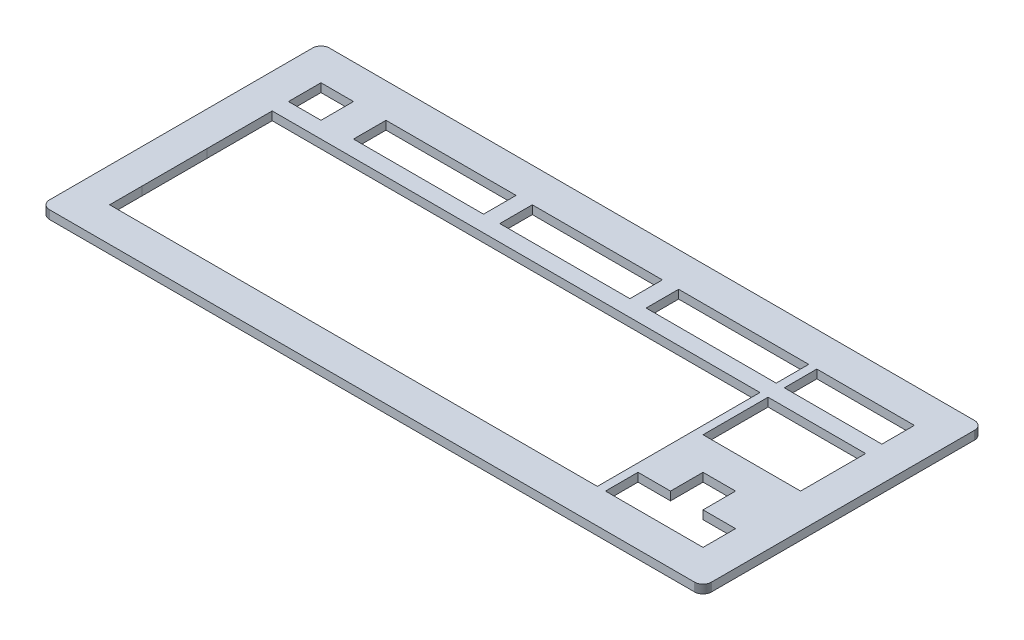
SolidWorks part; units mm, degrees
ref_plane "Front Plane" through (0, 0, 0) normal (0, 0, 1) x (1, 0, 0)
ref_plane "Top Plane" through (0, 0, 0) normal (0, 1, 0) x (1, 0, 0)
ref_plane "Right Plane" through (0, 0, 0) normal (1, 0, 0) x (0, 0, -1)
sketch "Sketch2" plane through (0, 0, 0) normal (0, 1, 0) x (1, 0, 0)
  line L0 (382.958, 164.299) -> (383.35, 164.284)
  line L1 (383.35, 164.284) -> (383.741, 164.237)
  line L2 (383.741, 164.237) -> (384.126, 164.162)
  line L3 (384.126, 164.162) -> (384.503, 164.055)
  line L4 (384.503, 164.055) -> (384.87, 163.919)
  line L5 (384.87, 163.919) -> (385.226, 163.755)
  line L6 (385.226, 163.755) -> (385.572, 163.564)
  line L7 (385.572, 163.564) -> (385.897, 163.344)
  line L8 (385.897, 163.344) -> (386.203, 163.102)
  line L9 (386.203, 163.102) -> (386.493, 162.834)
  line L10 (386.493, 162.834) -> (386.761, 162.547)
  line L11 (386.761, 162.547) -> (387.004, 162.238)
  line L12 (387.004, 162.238) -> (387.223, 161.913)
  line L13 (387.223, 161.913) -> (387.414, 161.569)
  line L14 (387.414, 161.569) -> (387.576, 161.212)
  line L15 (387.576, 161.212) -> (387.713, 160.845)
  line L16 (387.713, 160.845) -> (387.819, 160.467)
  line L17 (387.819, 160.467) -> (387.897, 160.082)
  line L18 (387.897, 160.082) -> (387.943, 159.693)
  line L19 (387.943, 159.693) -> (387.96, 159.299)
  line L20 (387.96, 159.299) -> (387.96, 5.2724)
  line L21 (387.96, 5.2724) -> (387.943, 4.881)
  line L22 (387.943, 4.881) -> (387.897, 4.491)
  line L23 (387.897, 4.491) -> (387.819, 4.1066)
  line L24 (387.819, 4.1066) -> (387.713, 3.7276)
  line L25 (387.713, 3.7276) -> (387.576, 3.3597)
  line L26 (387.576, 3.3597) -> (387.414, 3.0041)
  line L27 (387.414, 3.0041) -> (387.223, 2.661)
  line L28 (387.223, 2.661) -> (387.004, 2.3344)
  line L29 (387.004, 2.3344) -> (386.761, 2.0257)
  line L30 (386.761, 2.0257) -> (386.493, 1.7377)
  line L31 (386.493, 1.7377) -> (386.203, 1.4704)
  line L32 (386.203, 1.4704) -> (385.897, 1.2278)
  line L33 (385.897, 1.2278) -> (385.572, 1.0101)
  line L34 (385.572, 1.0101) -> (385.226, 0.8186)
  line L35 (385.226, 0.8186) -> (384.87, 0.6546)
  line L36 (384.87, 0.6546) -> (384.503, 0.5181)
  line L37 (384.503, 0.5181) -> (384.126, 0.412)
  line L38 (384.126, 0.412) -> (383.741, 0.3349)
  line L39 (383.741, 0.3349) -> (383.35, 0.2894)
  line L40 (383.35, 0.2894) -> (382.958, 0.2729)
  line L41 (382.958, 0.2729) -> (5.096, 0.2729)
  line L42 (5.096, 0.2729) -> (4.7019, 0.2894)
  line L43 (4.7019, 0.2894) -> (4.3119, 0.3349)
  line L44 (4.3119, 0.3349) -> (3.9274, 0.412)
  line L45 (3.9274, 0.412) -> (3.5498, 0.5181)
  line L46 (3.5498, 0.5181) -> (3.1819, 0.6546)
  line L47 (3.1819, 0.6546) -> (2.825, 0.8186)
  line L48 (2.825, 0.8186) -> (2.4819, 1.0101)
  line L49 (2.4819, 1.0101) -> (2.1566, 1.2278)
  line L50 (2.1566, 1.2278) -> (1.848, 1.4704)
  line L51 (1.848, 1.4704) -> (1.5599, 1.7377)
  line L52 (1.5599, 1.7377) -> (1.2926, 2.0257)
  line L53 (1.2926, 2.0257) -> (1.0501, 2.3344)
  line L54 (1.0501, 2.3344) -> (0.831, 2.661)
  line L55 (0.831, 2.661) -> (0.6394, 3.0041)
  line L56 (0.6394, 3.0041) -> (0.4754, 3.3597)
  line L57 (0.4754, 3.3597) -> (0.339, 3.7276)
  line L58 (0.339, 3.7276) -> (0.2329, 4.1066)
  line L59 (0.2329, 4.1066) -> (0.1571, 4.491)
  line L60 (0.1571, 4.491) -> (0.1102, 4.881)
  line L61 (0.1102, 4.881) -> (0.0951, 5.2737)
  line L62 (0.0951, 5.2737) -> (0.0951, 159.299)
  line L63 (0.0951, 159.299) -> (0.1102, 159.693)
  line L64 (0.1102, 159.693) -> (0.1571, 160.082)
  line L65 (0.1571, 160.082) -> (0.2329, 160.467)
  line L66 (0.2329, 160.467) -> (0.339, 160.845)
  line L67 (0.339, 160.845) -> (0.4754, 161.212)
  line L68 (0.4754, 161.212) -> (0.6394, 161.569)
  line L69 (0.6394, 161.569) -> (0.831, 161.913)
  line L70 (0.831, 161.913) -> (1.0501, 162.238)
  line L71 (1.0501, 162.238) -> (1.2926, 162.547)
  line L72 (1.2926, 162.547) -> (1.5599, 162.834)
  line L73 (1.5599, 162.834) -> (1.848, 163.102)
  line L74 (1.848, 163.102) -> (2.1566, 163.344)
  line L75 (2.1566, 163.344) -> (2.4819, 163.564)
  line L76 (2.4819, 163.564) -> (2.825, 163.755)
  line L77 (2.825, 163.755) -> (3.1819, 163.919)
  line L78 (3.1819, 163.919) -> (3.5498, 164.055)
  line L79 (3.5498, 164.055) -> (3.9274, 164.162)
  line L80 (3.9274, 164.162) -> (4.3119, 164.237)
  line L81 (4.3119, 164.237) -> (4.7019, 164.284)
  line L82 (4.7019, 164.284) -> (5.096, 164.299)
  line L83 (5.096, 164.299) -> (382.958, 164.299)
  line L84 (329.756, 58.4743) -> (329.756, 39.4243)
  line L85 (329.756, 39.4243) -> (310.706, 39.4243)
  line L86 (310.706, 39.4243) -> (310.706, 20.3729)
  line L87 (310.706, 20.3729) -> (367.859, 20.3729)
  line L88 (367.859, 20.3729) -> (367.859, 39.4243)
  line L89 (367.859, 39.4243) -> (348.809, 39.4243)
  line L90 (348.809, 39.4243) -> (348.809, 58.4743)
  line L91 (348.809, 58.4743) -> (329.756, 58.4743)
  line L92 (20.1952, 115.624) -> (20.1952, 77.5243)
  line L93 (20.1952, 77.5243) -> (20.1938, 77.5243)
  line L94 (20.1938, 77.5243) -> (20.1938, 39.4229)
  line L95 (20.1938, 39.4229) -> (20.1952, 39.4229)
  line L96 (20.1952, 39.4229) -> (20.1952, 20.3729)
  line L97 (20.1952, 20.3729) -> (305.947, 20.3729)
  line L98 (305.947, 20.3729) -> (305.947, 115.624)
  line L99 (305.947, 115.624) -> (20.1952, 115.624)
  line L100 (310.706, 115.624) -> (367.859, 115.624)
  line L101 (367.859, 115.624) -> (367.859, 77.5229)
  line L102 (367.859, 77.5229) -> (310.706, 77.5229)
  line L103 (310.706, 77.5229) -> (310.706, 115.624)
  line L104 (310.706, 144.199) -> (367.859, 144.199)
  line L105 (367.859, 144.199) -> (367.859, 125.149)
  line L106 (367.859, 125.149) -> (310.706, 125.149)
  line L107 (310.706, 125.149) -> (310.706, 144.199)
  line L108 (229.745, 144.199) -> (305.947, 144.199)
  line L109 (305.947, 144.199) -> (305.947, 125.149)
  line L110 (305.947, 125.149) -> (229.745, 125.149)
  line L111 (229.745, 125.149) -> (229.745, 144.199)
  line L112 (144.019, 144.199) -> (220.222, 144.199)
  line L113 (220.222, 144.199) -> (220.222, 125.149)
  line L114 (220.222, 125.149) -> (144.019, 125.149)
  line L115 (144.019, 125.149) -> (144.019, 144.199)
  line L116 (58.2951, 144.199) -> (134.497, 144.199)
  line L117 (134.497, 144.199) -> (134.497, 125.149)
  line L118 (134.497, 125.149) -> (58.2951, 125.149)
  line L119 (58.2951, 125.149) -> (58.2951, 144.199)
  line L120 (20.1952, 144.199) -> (39.2451, 144.199)
  line L121 (39.2451, 144.199) -> (39.2451, 125.149)
  line L122 (39.2451, 125.149) -> (20.1952, 125.149)
  line L123 (20.1952, 125.149) -> (20.1952, 144.199)
extrude "Boss-Extrude1" add sketch "Sketch2" along normal blind 5
